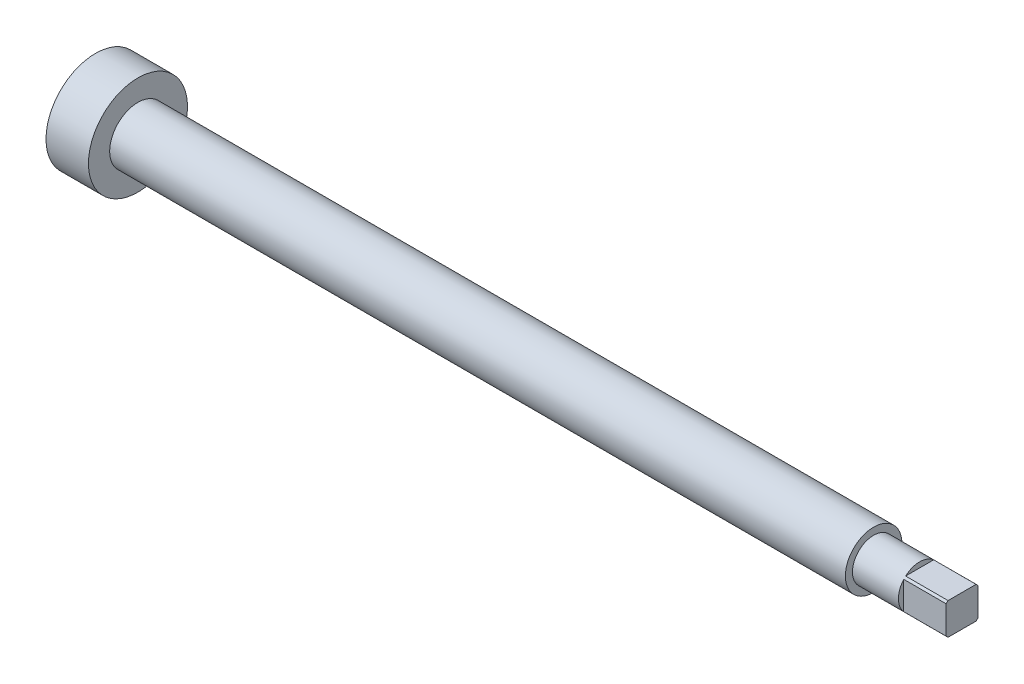
SolidWorks part; units mm, degrees
ref_plane "Front Plane" through (0, 0, 0) normal (0, 0, 1) x (1, 0, 0)
ref_plane "Top Plane" through (0, 0, 0) normal (0, 1, 0) x (1, 0, 0)
ref_plane "Right Plane" through (0, 0, 0) normal (1, 0, 0) x (0, 0, -1)
ref_plane "Plane1" through (0, 0, 0) normal (0, 0, 1) x (1, 0, 0)
sketch "Sketch1" plane through (0, 0, 0) normal (0, 0, 1) x (1, 0, 0)
  line L0 (-12, 0) -> (-12, 14)
  line L1 (-12, 14) -> (0, 14)
  line L2 (0, 14) -> (0, 8)
  line L3 (0, 8) -> (208, 8)
  line L4 (208, 8) -> (208, 6)
  line L5 (208, 6) -> (233, 6)
  line L6 (233, 6) -> (233, 0)
  line L7 (233, 0) -> (-12, 0)
  line L8 (500, 0) -> (-500, 0) construction
revolve "Revolve1" add sketch "Sketch1" angle 360 about L8
cosmetic thread "Cosmetic Thread1" parameters "D1"=208, "D2"=12.5
ref_plane "Plane2" through (221, 0, 0) normal (1, 0, 0) x (0, 0, -1)
sketch "Sketch2" plane through (221, 0, 0) normal (1, 0, 0) x (0, 0, -1)
  line L0 (-4.5, 4.5) -> (-4.5, -4.5)
  line L1 (-4.5, -4.5) -> (4.5, -4.5)
  line L2 (4.5, -4.5) -> (4.5, 4.5)
  line L3 (4.5, 4.5) -> (-4.5, 4.5)
  circle A0 centre (0, 0) radius 9
extrude "Cut-Extrude1" cut sketch "Sketch2" along normal blind 12
